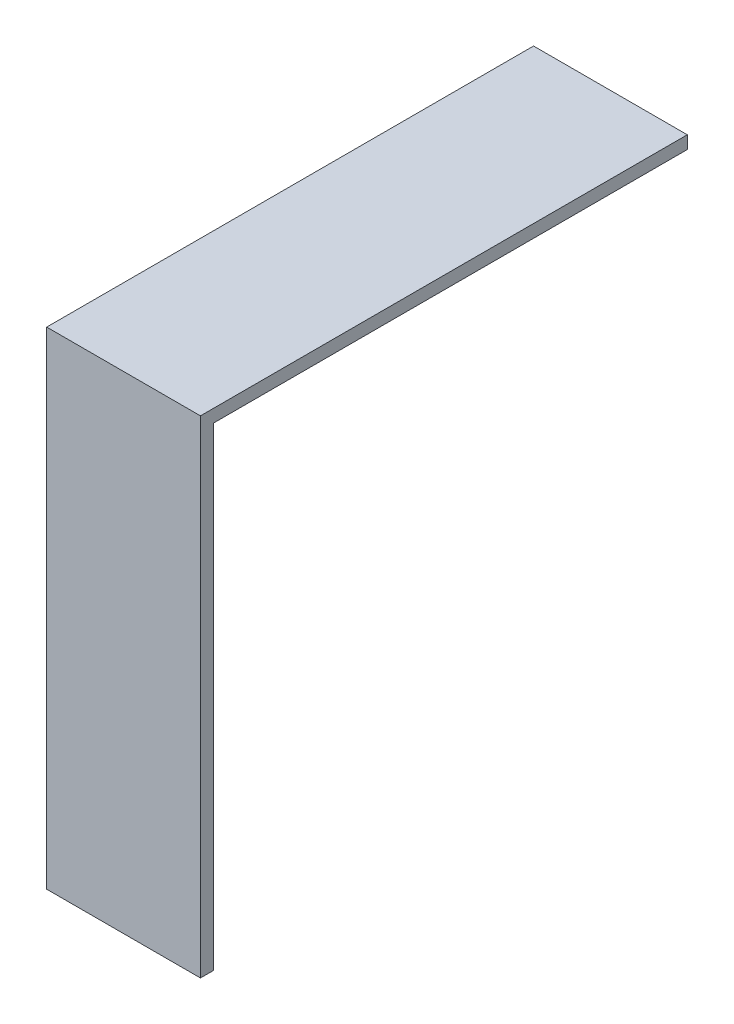
SolidWorks part; units mm, degrees
ref_plane "Front Plane" through (0, 0, 0) normal (0, 0, 1) x (1, 0, 0)
ref_plane "Top Plane" through (0, 0, 0) normal (0, 1, 0) x (1, 0, 0)
ref_plane "Right Plane" through (0, 0, 0) normal (1, 0, 0) x (0, 0, -1)
sketch "Sketch1" plane through (0, 0, 0) normal (1, 0, 0) x (0, 0, -1)
  line L0 (0, 0) -> (0, 120.65)
  line L1 (0, 120.65) -> (120.65, 120.65)
  line L2 (120.65, 120.65) -> (120.65, 117.475)
  line L3 (120.65, 117.475) -> (3.175, 117.475)
  line L4 (3.175, 117.475) -> (3.175, 0)
  line L5 (3.175, 0) -> (0, 0)
  dimension "D1" = 120.65
  dimension "D2" = 120.65
  dimension "D3" = 3.175
  dimension "D4" = 3.175
extrude "Boss-Extrude1" add sketch "Sketch1" along normal blind 38.1
